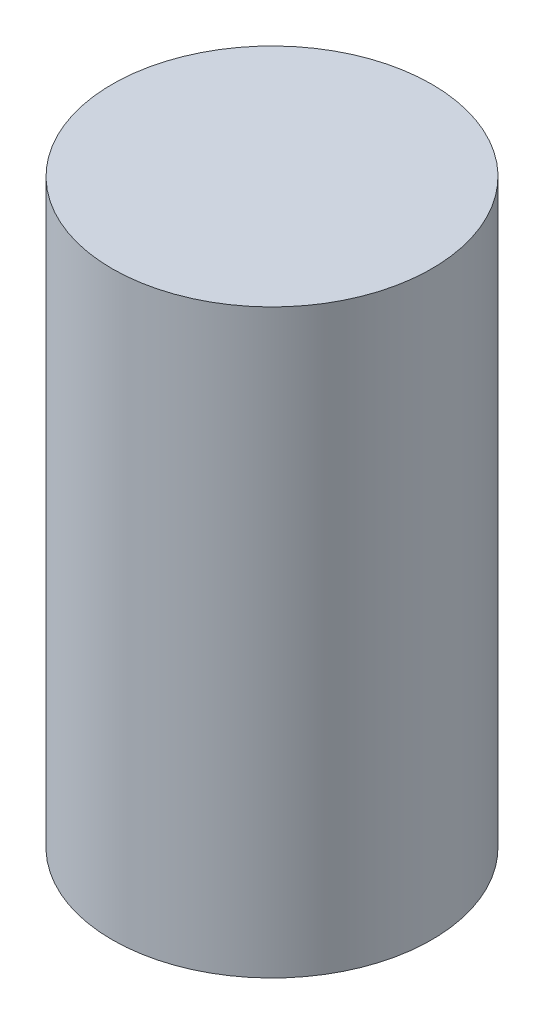
SolidWorks part; units mm, degrees
ref_plane "Front Plane" through (0, 0, 0) normal (0, 0, 1) x (1, 0, 0)
ref_plane "Top Plane" through (0, 0, 0) normal (0, 1, 0) x (1, 0, 0)
ref_plane "Right Plane" through (0, 0, 0) normal (1, 0, 0) x (0, 0, -1)
sketch "Sketch1" plane through (0, 0, 0) normal (0, 1, 0) x (1, 0, 0)
  circle A0 centre (0, 0) radius 11
extrude "Boss-Extrude1" add sketch "Sketch1" along normal blind 40
